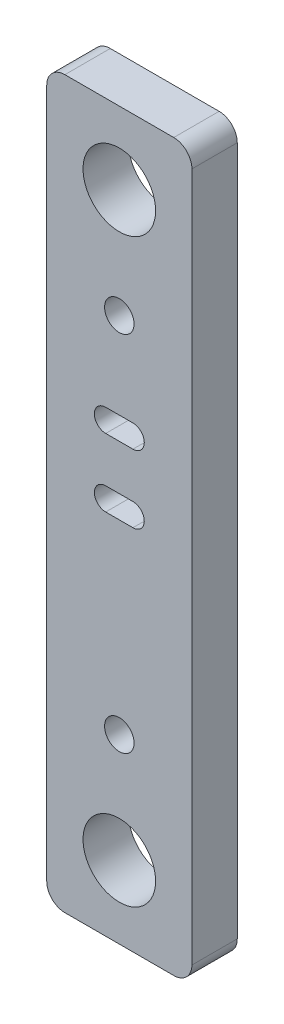
SolidWorks part; units mm, degrees
material "Maple"
ref_plane "Front Plane" through (0, 0, 0) normal (0, 0, 1) x (1, 0, 0)
ref_plane "Top Plane" through (0, 0, 0) normal (0, 1, 0) x (1, 0, 0)
ref_plane "Right Plane" through (0, 0, 0) normal (1, 0, 0) x (0, 0, -1)
sketch "Sketch1" plane through (0, 0, 0) normal (0, 0, 1) x (1, 0, 0)
  line L0 (8, 72) -> (8, 8) construction
  line L1 (0, 0) -> (16, 0)
  line L2 (0, 0) -> (0, 80)
  line L3 (0, 80) -> (16, 80)
  line L4 (16, 0) -> (16, 80)
  line L5 (8, 8) -> (8, 0) construction
  line L6 (6.5, 49.25) -> (9.5, 49.25) construction
  line L7 (6.5, 50.5) -> (9.5, 50.5)
  line L8 (6.5, 48) -> (9.5, 48)
  line L9 (6.5, 41.75) -> (9.5, 41.75) construction
  line L10 (6.5, 43) -> (9.5, 43)
  line L11 (6.5, 40.5) -> (9.5, 40.5)
  line L12 (8, 40) -> (16, 40) construction
  circle A0 centre (8, 72) radius 4
  circle A1 centre (8, 8) radius 4
  arc A2 (6.5, 50.5) -> (6.5, 48) centre (6.5, 49.25) ccw
  arc A3 (9.5, 48) -> (9.5, 50.5) centre (9.5, 49.25) ccw
  arc A4 (6.5, 43) -> (6.5, 40.5) centre (6.5, 41.75) ccw
  arc A5 (9.5, 40.5) -> (9.5, 43) centre (9.5, 41.75) ccw
  circle A6 centre (8, 20) radius 1.625
  circle A7 centre (8, 60) radius 1.625
  point P12 (8, 49.25)
  point P17 (8, 41.75)
  dimension "D2" = 8
  dimension "D10" = 3.25
  dimension "D1" = 8
  dimension "D3" = 64
  dimension "D4" = 8
  dimension "D5" = 8
  dimension "D6" = 8
  dimension "D7" = 3
  dimension "D8" = 2.5
  dimension "D9" = 5
  dimension "D11" = 12
  dimension "D12" = 12
extrude "Boss-Extrude1" add sketch "Sketch1" along normal blind 5
fillet "Fillet1" radius 2 4 edges at (0, 0, 2.5) (16, 0, 2.5) (16, 80, 2.5) (0, 80, 2.5)
